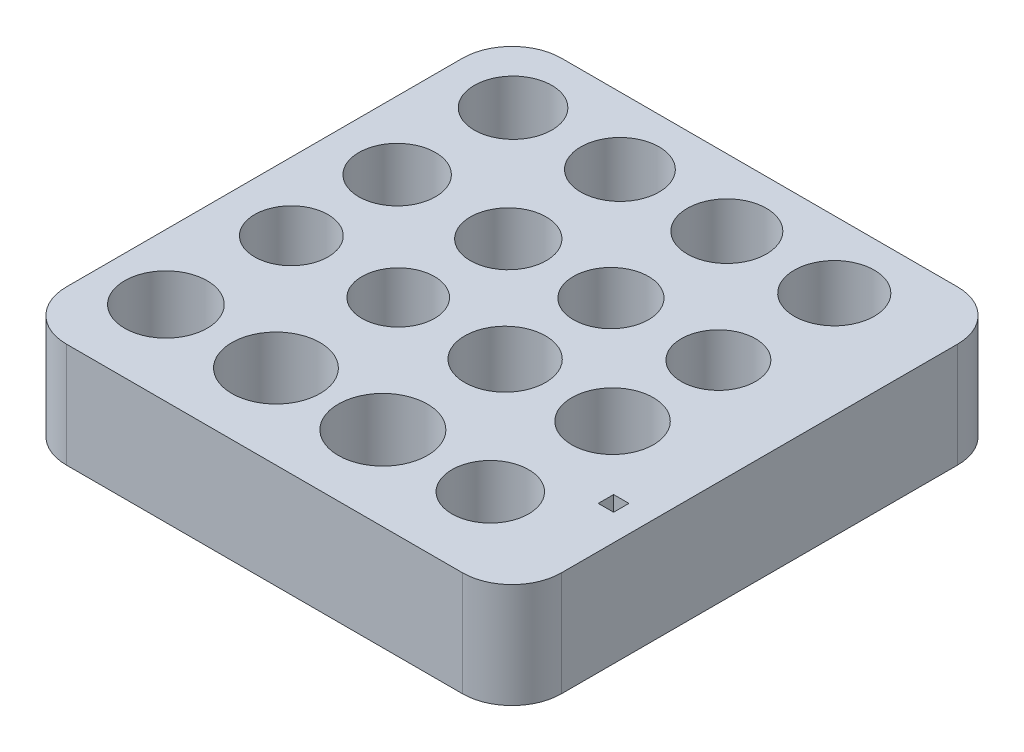
SolidWorks part; units mm, degrees
ref_plane "Front Plane" through (0, 0, 0) normal (0, 0, 1) x (1, 0, 0)
ref_plane "Top Plane" through (0, 0, 0) normal (0, 1, 0) x (1, 0, 0)
ref_plane "Right Plane" through (0, 0, 0) normal (1, 0, 0) x (0, 0, -1)
sketch "Sketch1" plane through (0, 0, 0) normal (0, 1, 0) x (1, 0, 0)
  line L1 (3, 0) -> (27, 0)
  line L2 (0, 3) -> (0, 27)
  line L3 (3, 30) -> (27, 30)
  line L4 (30, 3) -> (30, 27)
  arc A0 (3, 0) -> (0, 3) centre (3, 3) cw
  arc A1 (27, 0) -> (30, 3) centre (27, 3) ccw
  arc A2 (27, 30) -> (30, 27) centre (27, 27) cw
  arc A3 (0, 27) -> (3, 30) centre (3, 27) cw
  point P7 (0, 0)
  point P10 (30, 0)
  point P13 (30, 30)
  point P16 (0, 30)
  dimension "D3" = 3
  dimension "D1" = 30
  dimension "D2" = 30
extrude "Boss-Extrude1" add sketch "Sketch1" along normal blind 6.35
sketch "Sketch2" plane through (0, 6.35, 0) normal (0, 1, 0) x (1, 0, 0)
  line L1 (27.4728, 8.6834) -> (28.4026, 8.6834)
  line L2 (27.4728, 8.6834) -> (27.4728, 7.7536)
  line L3 (27.4728, 7.7536) -> (28.4026, 7.7536)
  line L4 (28.4026, 8.6834) -> (28.4026, 7.7536)
  circle A0 centre (4.1304, 25.9337) radius 2.35
  circle A1 centre (17.0841, 25.9337) radius 2.4
  circle A2 centre (4.1304, 18.9118) radius 2.325
  circle A3 centre (17.0841, 18.9118) radius 2.275
  circle A4 centre (10.6073, 25.9337) radius 2.375
  circle A5 centre (23.5931, 25.9337) radius 2.425
  circle A6 centre (10.8638, 18.9118) radius 2.3
  circle A7 centre (23.5931, 18.9118) radius 2.25
  circle A8 centre (4.1304, 12.499) radius 2.225
  circle A9 centre (10.6073, 12.499) radius 2.2
  circle A10 centre (17.0841, 12.499) radius 2.45
  circle A11 centre (23.5931, 12.499) radius 2.475
  circle A12 centre (3.938, 5.0923) radius 2.5
  circle A13 centre (10.6073, 5.0923) radius 2.675
  circle A14 centre (17.0841, 5.0923) radius 2.7
  circle A15 centre (23.5931, 5.0923) radius 2.325
  dimension "D1" = 4.7
  dimension "D2" = 4.8
  dimension "D3" = 4.65
  dimension "D4" = 4.55
  dimension "D5" = 4.75
  dimension "D6" = 4.85
  dimension "D7" = 4.6
  dimension "D8" = 4.5
  dimension "D9" = 4.45
  dimension "D10" = 4.4
  dimension "D11" = 4.9
  dimension "D12" = 4.95
  dimension "D13" = 5
  dimension "D14" = 5.35
  dimension "D15" = 5.4
  dimension "D16" = 4.65
extrude "Cut-Extrude1" cut sketch "Sketch2" against normal blind 6.35
